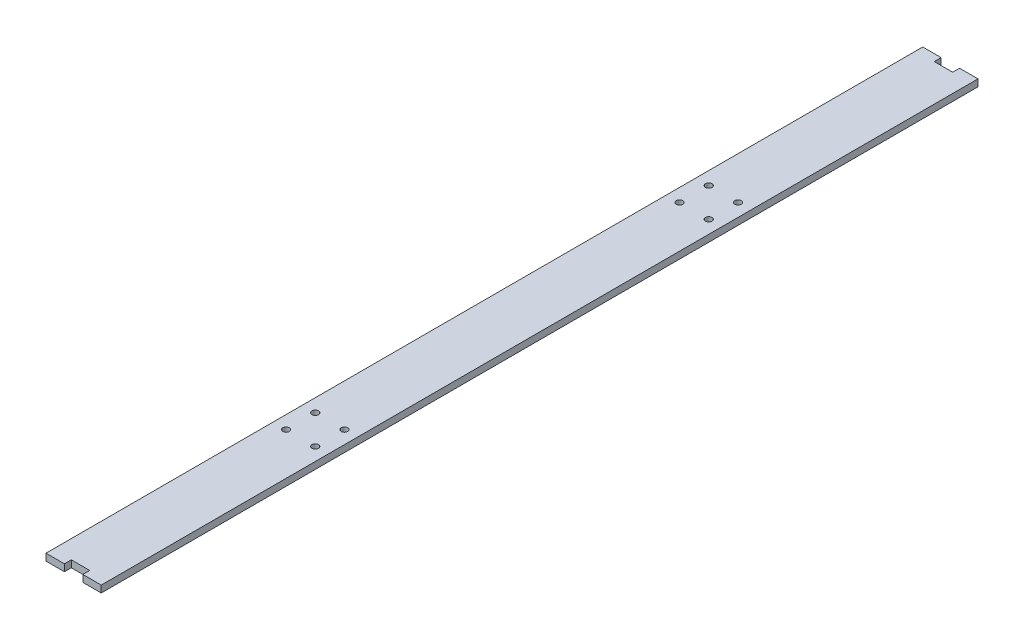
SolidWorks part; units mm, degrees
ref_plane "Front Plane" through (0, 0, 0) normal (0, 0, 1) x (1, 0, 0)
ref_plane "Top Plane" through (0, 0, 0) normal (0, 1, 0) x (1, 0, 0)
ref_plane "Right Plane" through (0, 0, 0) normal (1, 0, 0) x (0, 0, -1)
sketch "Sketch2" plane through (0, 0, 0) normal (0, 1, 0) x (1, 0, 0)
  line L1 (-12.7, -201.6125) -> (12.7, -201.6125)
  line L2 (-12.7, -201.6125) -> (-12.7, 201.6125)
  line L3 (-12.7, 201.6125) -> (12.7, 201.6125)
  line L4 (12.7, -201.6125) -> (12.7, 201.6125)
  line L5 (-12.7, -201.6125) -> (12.7, 201.6125) construction
  line L6 (-12.7, 201.6125) -> (12.7, -201.6125) construction
  point P0 (0, 0)
  dimension "D1" = 25.4
  dimension "D2" = 403.225
extrude "Boss-Extrude1" add sketch "Sketch2" along normal blind 3.175 contours L3 L4 L1 L2
sketch "Sketch3" plane through (0, 3.175, 0) normal (0, 1, 0) x (1, 0, 0)
  line L0 (-12.7, 201.6125) -> (12.7, 201.6125) construction
  line L1 (-4.2333, 201.6125) -> (4.2333, 201.6125)
  line L2 (-4.2333, 201.6125) -> (-4.2333, 198.4375)
  line L3 (-4.2333, 198.4375) -> (4.2333, 198.4375)
  line L4 (4.2333, 201.6125) -> (4.2333, 198.4375)
  line L5 (12.7, -201.6125) -> (12.7, 201.6125) construction
  dimension "D1" = 8.4667
  dimension "D2" = 3.175
  dimension "D3" = 8.4667
extrude "Cut-Extrude1" cut sketch "Sketch3" against normal blind 3.175
mirror "Mirror1" about plane through (0, 0, 0) normal (0, 0, 1) of "Cut-Extrude1"
sketch "Sketch4" plane through (0, 3.175, 0) normal (0, 1, 0) x (1, 0, 0)
  line L0 (-12.7, 1.5875) -> (12.7, 1.5875) construction
  line L1 (-12.7, -201.6125) -> (-12.7, 201.6125) construction
  line L2 (12.7, -201.6125) -> (12.7, 201.6125) construction
  line L3 (-4.2333, 198.4375) -> (4.2333, 198.4375) construction
  line L4 (-12.7, -1.5875) -> (12.7, -1.5875) construction
  line L5 (-4.2333, -198.4375) -> (4.2333, -198.4375) construction
  dimension "D1" = 196.85
  dimension "D2" = 196.85
sketch "Sketch5" plane through (0, 3.175, 0) normal (0, 1, 0) x (1, 0, 0)
  line L1 (-6.7175, -83.77) -> (6.7175, -83.77)
  line L2 (-6.7175, -83.77) -> (-6.7175, -97.205)
  line L3 (-6.7175, -97.205) -> (6.7175, -97.205)
  line L4 (6.7175, -83.77) -> (6.7175, -97.205)
  line L6 (-12.7, -1.5875) -> (12.7, -1.5875) construction
  circle A4 centre (-6.7175, -83.77) radius 1.5
  circle A5 centre (6.7175, -83.77) radius 1.5
  circle A6 centre (-6.7175, -97.205) radius 1.5
  circle A7 centre (6.7175, -97.205) radius 1.5
  point P4 (0, -83.77)
  point P11 (-6.7175, -90.4875)
  dimension "D2" = 3
  dimension "D1" = 19
  dimension "D3" = 88.9
extrude "Cut-Extrude2" cut sketch "Sketch5" against normal blind 3.175 contours L4 A5 L1 | L1 A5 L4 | L1 A4 L2 | L2 A6 L3 | L3 A7 L4 | L2 A4 L1 | L3 A6 L2 | L4 A7 L3
mirror "Mirror2" about plane through (0, 0, 0) normal (0, 0, 1) of "Cut-Extrude2"
